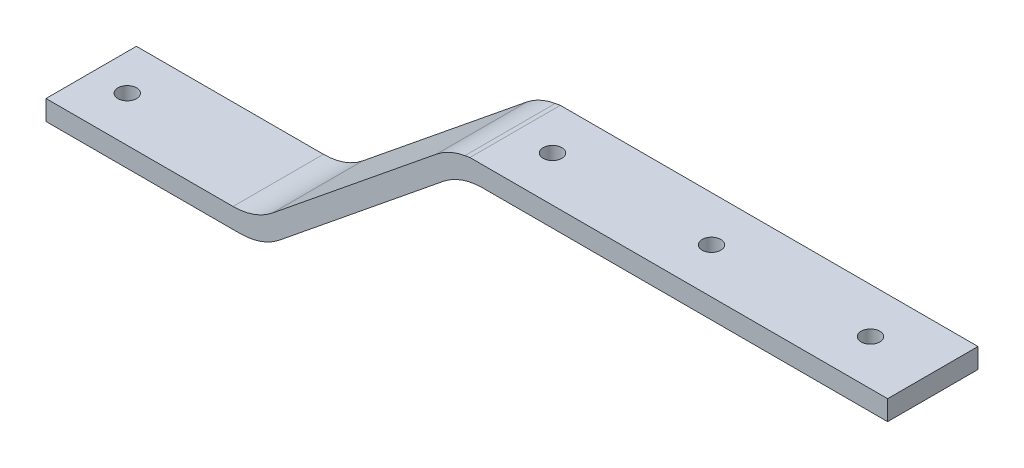
SolidWorks part; units mm, degrees
ref_plane "Front Plane" through (0, 0, 0) normal (0, 0, 1) x (1, 0, 0)
ref_plane "Top Plane" through (0, 0, 0) normal (0, 1, 0) x (1, 0, 0)
ref_plane "Right Plane" through (0, 0, 0) normal (1, 0, 0) x (0, 0, -1)
sketch "Sketch2" plane through (0, 0, 0) normal (0, 0, 1) x (1, 0, 0)
  line L0 (0, 41.3604) -> (67, 41.3604)
  line L1 (67, 41.3604) -> (67, 38.1604)
  line L2 (67, 38.1604) -> (2.0442, 38.1604)
  line L3 (-4.2538, 35.928) -> (-30.5678, 14.5927)
  line L4 (-36.8657, 12.3604) -> (-68, 12.3604)
  line L5 (-68, 12.3604) -> (-68, 15.5604)
  line L6 (-68, 15.5604) -> (-38, 15.5604)
  line L7 (-31.7021, 17.7927) -> (-5.3772, 39.1367)
  line L8 (-0.8077, 41.2186) -> (0, 41.3604)
  arc A0 (-30.5678, 14.5927) -> (-36.8657, 12.3604) centre (-36.8657, 22.3604) cw
  arc A1 (2.0442, 38.1604) -> (-4.2538, 35.928) centre (2.0442, 28.1604) ccw
  arc A2 (-5.3772, 39.1367) -> (-0.8077, 41.2186) centre (0.9207, 31.3691) cw
  arc A3 (-38, 15.5604) -> (-31.7021, 17.7927) centre (-38, 25.5604) ccw
  dimension "D7" = 10
  dimension "D1" = 29
  dimension "D2" = 3.2
  dimension "D3" = 3.2
  dimension "D4" = 3.2
  dimension "D5" = 135
  dimension "D6" = 67
  dimension "D8" = 30
extrude "Boss-Extrude1" add sketch "Sketch2" along normal blind 14.5
sketch "Sketch3" plane through (0, 41.3604, 0) normal (0, 1, 0) x (1, 0, 0)
  line L0 (67, -14.5) -> (0, -14.5) construction
  line L1 (67, -14.5) -> (67, 0) construction
  circle A0 centre (6, -7.25) radius 1.5
  circle A1 centre (31.5, -7.25) radius 1.5
  circle A2 centre (57, -7.25) radius 1.5
  circle A3 centre (-62.2149, -7.25) radius 1.5
  dimension "D1" = 3
  dimension "D8" = 3
  dimension "D2" = 7.25
  dimension "D3" = 7.25
  dimension "D4" = 7.25
  dimension "D5" = 25.5
  dimension "D6" = 25.5
  dimension "D7" = 10
extrude "Cut-Extrude1" cut sketch "Sketch3" against normal through all
